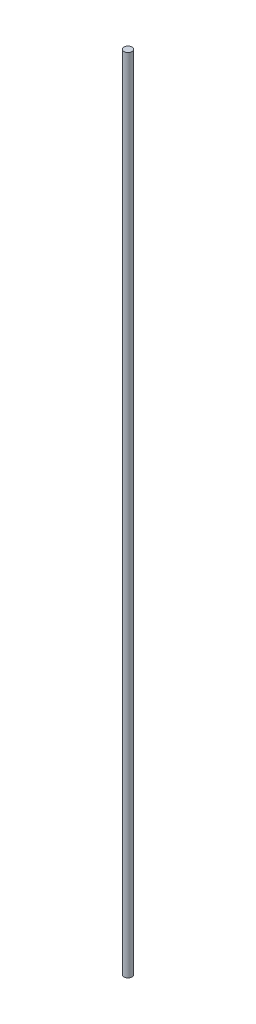
SolidWorks part; units mm, degrees
material "AISI 1020"
ref_plane "Front Plane" through (0, 0, 0) normal (0, 0, 1) x (1, 0, 0)
ref_plane "Top Plane" through (0, 0, 0) normal (0, 1, 0) x (1, 0, 0)
ref_plane "Right Plane" through (0, 0, 0) normal (1, 0, 0) x (0, 0, -1)
sketch "Sketch1" plane through (0, 0, 0) normal (0, 1, 0) x (1, 0, 0)
  circle A0 centre (0, 0) radius 2
  dimension "D1" = 4
extrude "Boss-Extrude2" add sketch "Sketch1" along normal blind 400
cosmetic thread "Cosmetic Thread1" parameters "D2"=3.22
